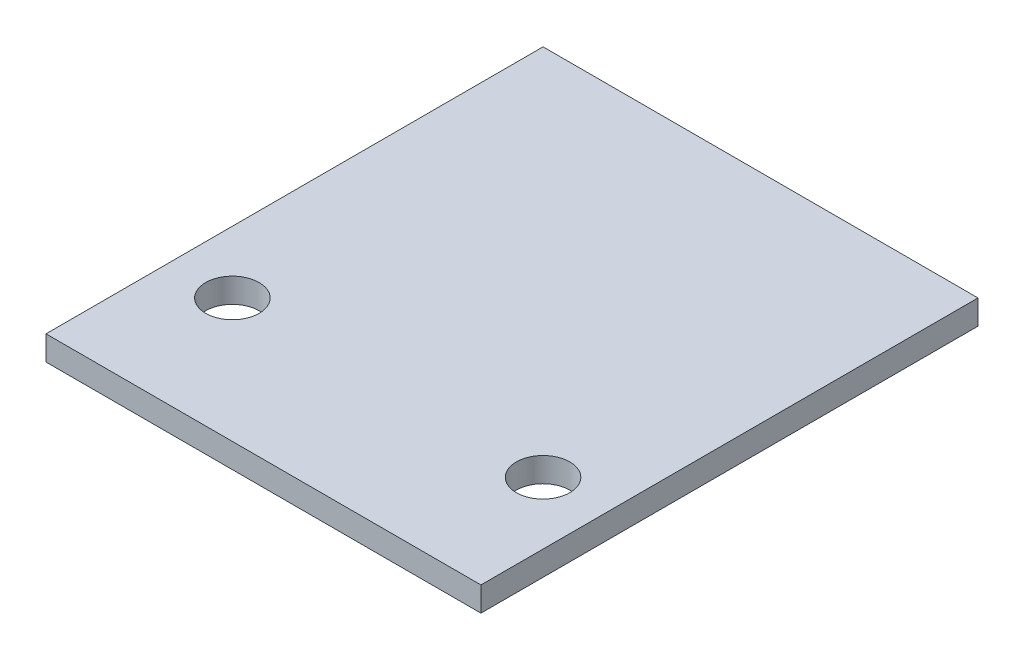
SolidWorks part; units mm, degrees
ref_plane "Front Plane" through (0, 0, 0) normal (0, 0, 1) x (1, 0, 0)
ref_plane "Top Plane" through (0, 0, 0) normal (0, 1, 0) x (1, 0, 0)
ref_plane "Right Plane" through (0, 0, 0) normal (1, 0, 0) x (0, 0, -1)
sketch "Sketch1" plane through (0, 0, 0) normal (0, 1, 0) x (1, 0, 0)
  line L1 (-8.89, 10.16) -> (8.89, 10.16)
  line L2 (-8.89, 10.16) -> (-8.89, -10.16)
  line L3 (-8.89, -10.16) -> (8.89, -10.16)
  line L4 (8.89, 10.16) -> (8.89, -10.16)
  line L5 (-8.89, 10.16) -> (8.89, -10.16) construction
  line L6 (-8.89, -10.16) -> (8.89, 10.16) construction
  point P0 (0, 0)
  dimension "D1" = 17.78
  dimension "D2" = 20.32
extrude "Boss-Extrude1" add sketch "Sketch1" along normal blind 1
sketch "Sketch2" plane through (0, 1, 0) normal (0, 1, 0) x (1, 0, 0)
  line L0 (-6.35, -5.08) -> (6.35, -5.08) construction
  line L1 (0, -5.08) -> (0, 10.16) construction
  line L2 (8.89, 10.16) -> (-8.89, 10.16) construction
  dimension "D1" = 15.24
  dimension "D2" = 12.7
hole_wizard "#2 Clearance Hole1" positions "Sketch3" profile "Sketch4" hole size "#2" standard "ANSI Inch" end condition through all
sketch "Sketch3" plane through (0, 1, 0) normal (0, 1, 0) x (1, 0, 0)
  point P0 (-6.35, -5.08)
  point P3 (6.35, -5.08)
sketch "Sketch4" plane through (-6.35, 1, 5.08) normal (1, 0, 0) x (0, 0, 1)
  line L0 (0, 0) -> (0, 1)
  line L1 (0, 1) -> (1.0922, 1)
  line L2 (1.0922, 1) -> (1.0922, 0)
  line L5 (1.0922, 0) -> (0, 0)
  line L11 (0, -6.35) -> (0, 107.95) construction
  dimension "Thru Hole Dia." = 2.1844
  dimension "Thru Hole Depth" = 1
